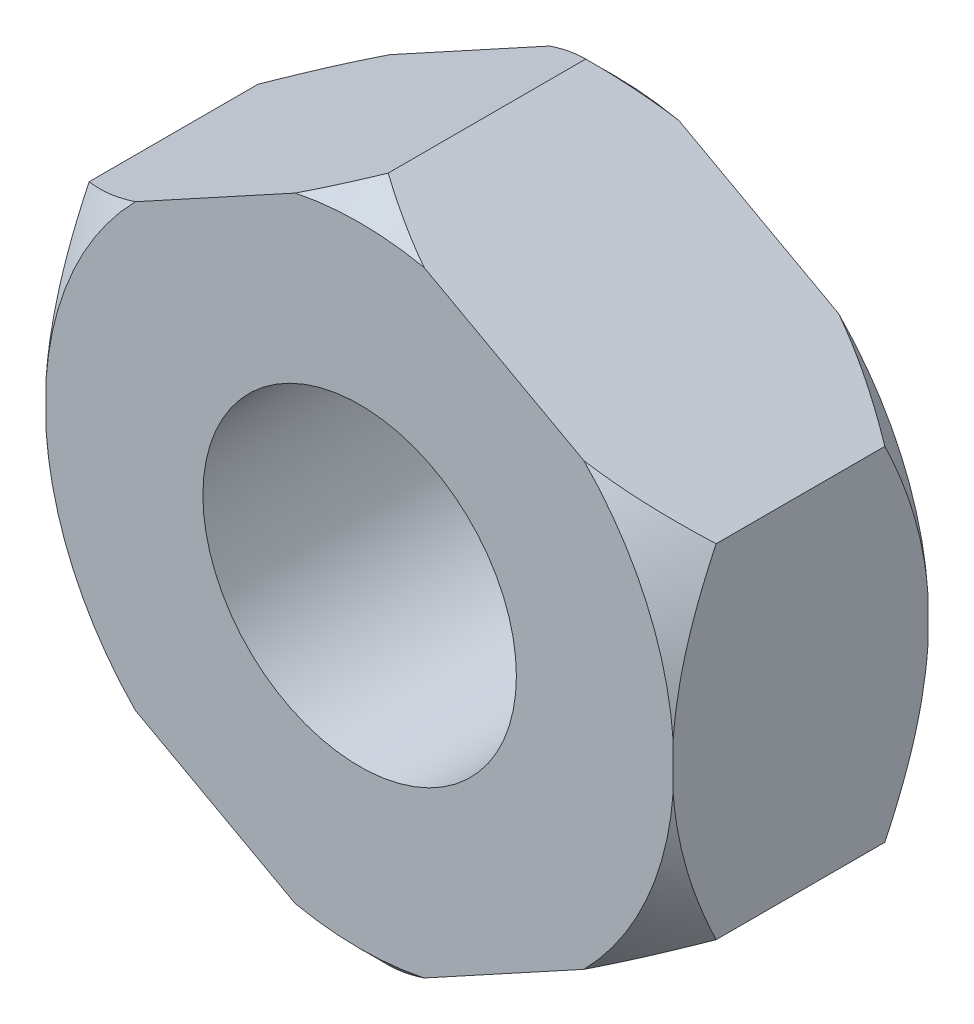
SolidWorks part; units mm, degrees
ref_plane "Front Plane" through (0, 0, 0) normal (0, 0, 1) x (1, 0, 0)
ref_plane "Top Plane" through (0, 0, 0) normal (0, 1, 0) x (1, 0, 0)
ref_plane "Right Plane" through (0, 0, 0) normal (1, 0, 0) x (0, 0, -1)
sketch "Sketch1" plane through (0, 0, 0) normal (0, 0, 1) x (1, 0, 0)
  line L0 (0, 0) -> (0, 1.75) construction
  line L1 (-1.6, -0.875) -> (-1.6, 0.875)
  line L2 (0, 0) -> (0, -1.75) construction
  line L3 (0, 0) -> (-1.6, 0) construction
  line L4 (1.6, -0.875) -> (1.6, 0.875)
  line L5 (-1.6, 0.875) -> (0, 1.75)
  line L6 (0, 1.75) -> (1.6, 0.875)
  line L7 (1.6, -0.875) -> (0, -1.75)
  line L8 (0, -1.75) -> (-1.6, -0.875)
  circle A0 centre (0, 0) radius 0.8
  dimension "D1" = 1.75
  dimension "D2" = 1.6
  dimension "THREAD SIZE" = 1.6
  dimension "D3" = 0.875
  dimension "LENGTH (A)" = 3.2
  dimension "D4" = 0.875
  dimension "HEIGHT (B)" = 3.5
  dimension "D5" = 1.75
  dimension "D6" = 90
extrude "NUT" add sketch "Sketch1" along normal blind 1.3
sketch "Sketch2" plane through (0, 0, 0) normal (1, 0, 0) x (0, 0, -1)
  line L0 (-1.3, 1.6042) -> (-0.6666, 2.2376)
  line L1 (-1.3, 0.875) -> (-1.3, 1.75) construction
  line L2 (-1.3, 1.75) -> (0, 1.75) construction
  line L3 (-1.3, 1.6042) -> (-1.3, 1.75)
  line L4 (0, 2.2376) -> (-0.6334, 2.2376)
  line L5 (-0.65, 1.75) -> (-0.65, 1.4914) construction
  line L6 (0, 1.75) -> (0, 2.2376)
  line L7 (0, 1.6042) -> (0, 1.75)
  line L8 (-1.3, 1.75) -> (-1.3, 2.2376)
  line L9 (0, 1.6042) -> (-0.6334, 2.2376)
  line L10 (-1.3, 2.2376) -> (-0.6666, 2.2376)
  dimension "D1" = 0.8958
  dimension "D2" = 0.1458
  dimension "D3" = 45
revolve "Cut-Revolve1" cut sketch "Sketch2" angle 360 about axis through (0, 0, 1.3) along (0, 0, -1)
equation "\"D3@SKETCH1\"=\"HEIGHT (B)@SKETCH1\"/4"
equation "\"D4@SKETCH1\"=\"HEIGHT (B)@SKETCH1\"/4"
equation "\"D1@SKETCH1\"=\"HEIGHT (B)@SKETCH1\"/2"
equation "\"D2@SKETCH1\"=\"LENGTH (A)@SKETCH1\"/2"
equation "\"D5@SKETCH1\"=\"D1@SKETCH1\""
equation "\"d2@sketch2\"=\"height (b)@sketch1\"/24"
equation "\"D1@SKETCH2\"=\"D2@SKETCH2\"+.75"
